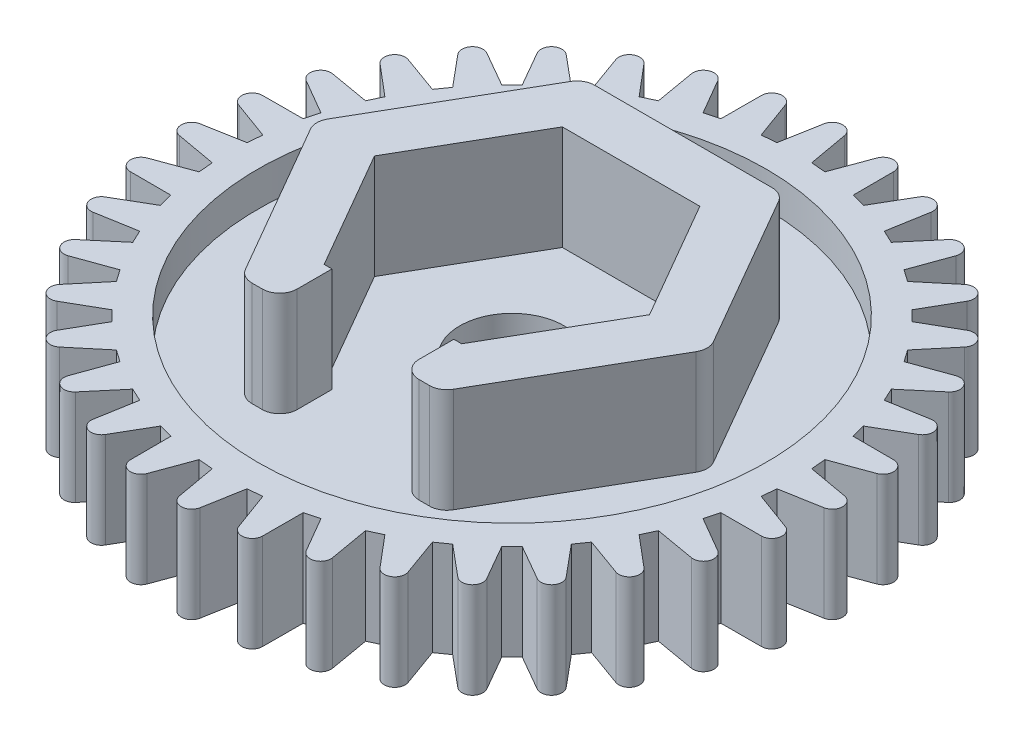
SolidWorks part; units mm, degrees
material "ABS"
ref_plane "Plano frontal" through (0, 0, 0) normal (0, 0, 1) x (1, 0, 0)
ref_plane "Plano superior" through (0, 0, 0) normal (0, 1, 0) x (1, 0, 0)
ref_plane "Plano direito" through (0, 0, 0) normal (1, 0, 0) x (0, 0, -1)
ref_plane "Plano1" through (0, 1, 0) normal (0, 1, 0) x (1, 0, 0)
sketch "Esboço1" plane through (0, 1, 0) normal (0, 1, 0) x (1, 0, 0)
  line L0 (-8.7959, 2.8872) -> (-7.9008, 2.3673)
  line L1 (-7.9008, 2.3673) -> (-7.8996, 1.9006)
  line L2 (-7.8996, 1.9006) -> (-9.061, 1.8976)
  line L3 (-9.1636, 1.3159) -> (-8.0732, 0.9158)
  line L4 (-8.0732, 0.9158) -> (-8.1096, 0.5)
  line L5 (-8.1096, 0.5) -> (-9.2529, 0.2953)
  line L6 (-9.2529, -0.2953) -> (-8.1096, -0.5)
  line L7 (-8.1096, -0.5) -> (-8.0732, -0.9158)
  line L8 (-8.0732, -0.9158) -> (-9.1636, -1.3159)
  line L9 (-9.061, -1.8976) -> (-7.8996, -1.9006)
  line L10 (-7.8996, -1.9006) -> (-7.9008, -2.3673)
  line L11 (-7.9008, -2.3673) -> (-8.7959, -2.8872)
  line L12 (-8.5939, -3.4422) -> (-7.4495, -3.2435)
  line L13 (-7.4495, -3.2435) -> (-7.2731, -3.6218)
  line L14 (-7.2731, -3.6218) -> (-8.1609, -4.3707)
  line L15 (-7.8656, -4.8822) -> (-6.7731, -4.4878)
  line L16 (-6.7731, -4.4878) -> (-6.5337, -4.8297)
  line L17 (-6.5337, -4.8297) -> (-7.2779, -5.7214)
  line L18 (-6.8983, -6.1738) -> (-5.8909, -5.5958)
  line L19 (-5.8909, -5.5958) -> (-5.5958, -5.8909)
  line L20 (-5.5958, -5.8909) -> (-6.1738, -6.8983)
  line L21 (-5.7214, -7.2779) -> (-4.8297, -6.5337)
  line L22 (-4.8297, -6.5337) -> (-4.4878, -6.7731)
  line L23 (-4.4878, -6.7731) -> (-4.8822, -7.8656)
  line L24 (-4.3707, -8.1609) -> (-3.6218, -7.2731)
  line L25 (-3.6218, -7.2731) -> (-3.2435, -7.4495)
  line L26 (-3.2435, -7.4495) -> (-3.4422, -8.5939)
  line L27 (-2.8872, -8.7959) -> (-2.3673, -7.9008)
  line L28 (-2.3673, -7.9008) -> (-1.9006, -7.8996)
  line L29 (-1.9006, -7.8996) -> (-1.8976, -9.061)
  line L30 (-1.3159, -9.1636) -> (-0.9158, -8.0732)
  line L31 (-0.9158, -8.0732) -> (-0.5, -8.1096)
  line L32 (-0.5, -8.1096) -> (-0.2953, -9.2529)
  line L33 (0.2953, -9.2529) -> (0.5, -8.1096)
  line L34 (0.5, -8.1096) -> (0.9158, -8.0732)
  line L35 (0.9158, -8.0732) -> (1.3159, -9.1636)
  line L36 (1.8976, -9.061) -> (1.9006, -7.8996)
  line L37 (1.9006, -7.8996) -> (2.3673, -7.9008)
  line L38 (2.3673, -7.9008) -> (2.8872, -8.7959)
  line L39 (3.4422, -8.5939) -> (3.2435, -7.4495)
  line L40 (3.2435, -7.4495) -> (3.6218, -7.2731)
  line L41 (3.6218, -7.2731) -> (4.3707, -8.1609)
  line L42 (4.8822, -7.8656) -> (4.4878, -6.7731)
  line L43 (4.4878, -6.7731) -> (4.8297, -6.5337)
  line L44 (4.8297, -6.5337) -> (5.7214, -7.2779)
  line L45 (6.1738, -6.8983) -> (5.5958, -5.8909)
  line L46 (5.5958, -5.8909) -> (5.8909, -5.5958)
  line L47 (5.8909, -5.5958) -> (6.8983, -6.1738)
  line L48 (7.2779, -5.7214) -> (6.5337, -4.8297)
  line L49 (6.5337, -4.8297) -> (6.7731, -4.4878)
  line L50 (6.7731, -4.4878) -> (7.8656, -4.8822)
  line L51 (8.1609, -4.3707) -> (7.2731, -3.6218)
  line L52 (7.2731, -3.6218) -> (7.4495, -3.2435)
  line L53 (7.4495, -3.2435) -> (8.5939, -3.4422)
  line L54 (8.7959, -2.8872) -> (7.9008, -2.3673)
  line L55 (7.9008, -2.3673) -> (7.8996, -1.9006)
  line L56 (7.8996, -1.9006) -> (9.061, -1.8976)
  line L57 (9.1636, -1.3159) -> (8.0732, -0.9158)
  line L58 (8.0732, -0.9158) -> (8.1096, -0.5)
  line L59 (8.1096, -0.5) -> (9.2529, -0.2953)
  line L60 (9.2529, 0.2953) -> (8.1096, 0.5)
  line L61 (8.1096, 0.5) -> (8.0732, 0.9158)
  line L62 (8.0732, 0.9158) -> (9.1636, 1.3159)
  line L63 (9.061, 1.8976) -> (7.8996, 1.9006)
  line L64 (7.8996, 1.9006) -> (7.9008, 2.3673)
  line L65 (7.9008, 2.3673) -> (8.7959, 2.8872)
  line L66 (8.5939, 3.4422) -> (7.4495, 3.2435)
  line L67 (7.4495, 3.2435) -> (7.2731, 3.6218)
  line L68 (7.2731, 3.6218) -> (8.1609, 4.3707)
  line L69 (7.8656, 4.8822) -> (6.7731, 4.4878)
  line L70 (6.7731, 4.4878) -> (6.5337, 4.8297)
  line L71 (6.5337, 4.8297) -> (7.2779, 5.7214)
  line L72 (6.8983, 6.1738) -> (5.8909, 5.5958)
  line L73 (5.8909, 5.5958) -> (5.5958, 5.8909)
  line L74 (5.5958, 5.8909) -> (6.1738, 6.8983)
  line L75 (5.7214, 7.2779) -> (4.8297, 6.5337)
  line L76 (4.8297, 6.5337) -> (4.4878, 6.7731)
  line L77 (4.4878, 6.7731) -> (4.8822, 7.8656)
  line L78 (4.3707, 8.1609) -> (3.6218, 7.2731)
  line L79 (3.6218, 7.2731) -> (3.2435, 7.4495)
  line L80 (3.2435, 7.4495) -> (3.4422, 8.5939)
  line L81 (2.8872, 8.7959) -> (2.3673, 7.9008)
  line L82 (2.3673, 7.9008) -> (1.9006, 7.8996)
  line L83 (1.9006, 7.8996) -> (1.8976, 9.061)
  line L84 (1.3159, 9.1636) -> (0.9158, 8.0732)
  line L85 (0.9158, 8.0732) -> (0.5, 8.1096)
  line L86 (0.5, 8.1096) -> (0.2953, 9.2529)
  line L87 (-0.2953, 9.2529) -> (-0.5, 8.1096)
  line L88 (-0.5, 8.1096) -> (-0.9158, 8.0732)
  line L89 (-0.9158, 8.0732) -> (-1.3159, 9.1636)
  line L90 (-1.8976, 9.061) -> (-1.9006, 7.8996)
  line L91 (-1.9006, 7.8996) -> (-2.3673, 7.9008)
  line L92 (-2.3673, 7.9008) -> (-2.8872, 8.7959)
  line L93 (-3.4422, 8.5939) -> (-3.2435, 7.4495)
  line L94 (-3.2435, 7.4495) -> (-3.6218, 7.2731)
  line L95 (-3.6218, 7.2731) -> (-4.3707, 8.1609)
  line L96 (-4.8822, 7.8656) -> (-4.4878, 6.7731)
  line L97 (-4.4878, 6.7731) -> (-4.8297, 6.5337)
  line L98 (-4.8297, 6.5337) -> (-5.7214, 7.2779)
  line L99 (-6.1738, 6.8983) -> (-5.5958, 5.8909)
  line L100 (-5.5958, 5.8909) -> (-5.8909, 5.5958)
  line L101 (-5.8909, 5.5958) -> (-6.8983, 6.1738)
  line L102 (-7.2779, 5.7214) -> (-6.5337, 4.8297)
  line L103 (-6.5337, 4.8297) -> (-6.7731, 4.4878)
  line L104 (-6.7731, 4.4878) -> (-7.8656, 4.8822)
  line L105 (-8.1609, 4.3707) -> (-7.2731, 3.6218)
  line L106 (-7.2731, 3.6218) -> (-7.4495, 3.2435)
  line L107 (-7.4495, 3.2435) -> (-8.5939, 3.4422)
  arc A0 (-9.061, 1.8976) -> (-9.1636, 1.3159) centre (-9.0602, 1.5976) ccw
  arc A1 (-9.2529, 0.2953) -> (-9.2529, -0.2953) centre (-9.2, 0) ccw
  arc A2 (-9.1636, -1.3159) -> (-9.061, -1.8976) centre (-9.0602, -1.5976) ccw
  arc A3 (-8.7959, -2.8872) -> (-8.5939, -3.4422) centre (-8.6452, -3.1466) ccw
  arc A4 (-8.1609, -4.3707) -> (-7.8656, -4.8822) centre (-7.9674, -4.6) ccw
  arc A5 (-7.2779, -5.7214) -> (-6.8983, -6.1738) centre (-7.0476, -5.9136) ccw
  arc A6 (-6.1738, -6.8983) -> (-5.7214, -7.2779) centre (-5.9136, -7.0476) ccw
  arc A7 (-4.8822, -7.8656) -> (-4.3707, -8.1609) centre (-4.6, -7.9674) ccw
  arc A8 (-3.4422, -8.5939) -> (-2.8872, -8.7959) centre (-3.1466, -8.6452) ccw
  arc A9 (-1.8976, -9.061) -> (-1.3159, -9.1636) centre (-1.5976, -9.0602) ccw
  arc A10 (-0.2953, -9.2529) -> (0.2953, -9.2529) centre (0, -9.2) ccw
  arc A11 (1.3159, -9.1636) -> (1.8976, -9.061) centre (1.5976, -9.0602) ccw
  arc A12 (2.8872, -8.7959) -> (3.4422, -8.5939) centre (3.1466, -8.6452) ccw
  arc A13 (4.3707, -8.1609) -> (4.8822, -7.8656) centre (4.6, -7.9674) ccw
  arc A14 (5.7214, -7.2779) -> (6.1738, -6.8983) centre (5.9136, -7.0476) ccw
  arc A15 (6.8983, -6.1738) -> (7.2779, -5.7214) centre (7.0476, -5.9136) ccw
  arc A16 (7.8656, -4.8822) -> (8.1609, -4.3707) centre (7.9674, -4.6) ccw
  arc A17 (8.5939, -3.4422) -> (8.7959, -2.8872) centre (8.6452, -3.1466) ccw
  arc A18 (9.061, -1.8976) -> (9.1636, -1.3159) centre (9.0602, -1.5976) ccw
  arc A19 (9.2529, -0.2953) -> (9.2529, 0.2953) centre (9.2, 0) ccw
  arc A20 (9.1636, 1.3159) -> (9.061, 1.8976) centre (9.0602, 1.5976) ccw
  arc A21 (8.7959, 2.8872) -> (8.5939, 3.4422) centre (8.6452, 3.1466) ccw
  arc A22 (8.1609, 4.3707) -> (7.8656, 4.8822) centre (7.9674, 4.6) ccw
  arc A23 (7.2779, 5.7214) -> (6.8983, 6.1738) centre (7.0476, 5.9136) ccw
  arc A24 (6.1738, 6.8983) -> (5.7214, 7.2779) centre (5.9136, 7.0476) ccw
  arc A25 (4.8822, 7.8656) -> (4.3707, 8.1609) centre (4.6, 7.9674) ccw
  arc A26 (3.4422, 8.5939) -> (2.8872, 8.7959) centre (3.1466, 8.6452) ccw
  arc A27 (1.8976, 9.061) -> (1.3159, 9.1636) centre (1.5976, 9.0602) ccw
  arc A28 (0.2953, 9.2529) -> (-0.2953, 9.2529) centre (0, 9.2) ccw
  arc A29 (-1.3159, 9.1636) -> (-1.8976, 9.061) centre (-1.5976, 9.0602) ccw
  arc A30 (-2.8872, 8.7959) -> (-3.4422, 8.5939) centre (-3.1466, 8.6452) ccw
  arc A31 (-4.3707, 8.1609) -> (-4.8822, 7.8656) centre (-4.6, 7.9674) ccw
  arc A32 (-5.7214, 7.2779) -> (-6.1738, 6.8983) centre (-5.9136, 7.0476) ccw
  arc A33 (-6.8983, 6.1738) -> (-7.2779, 5.7214) centre (-7.0476, 5.9136) ccw
  arc A34 (-7.8656, 4.8822) -> (-8.1609, 4.3707) centre (-7.9674, 4.6) ccw
  arc A35 (-8.5939, 3.4422) -> (-8.7959, 2.8872) centre (-8.6452, 3.1466) ccw
extrude "Ressalto-extrusão1" add sketch "Esboço1" against normal blind 2.75
hole_wizard "Furo com folga de M121" positions "Esboço3" profile "Esboço2" hole size "M12" standard "Ansi Metric"
sketch "Esboço3" plane through (0, 1, 0) normal (0, 1, 0) x (1, 0, 0)
  point P0 (0, 0)
sketch "Esboço2" plane through (0, 1, 0) normal (1, 0, 0) x (0, 0, 1)
  line L0 (0, 0) -> (0, 1)
  line L1 (0, 1) -> (7.3, 1)
  line L2 (7.3, 1) -> (7.3, 0)
  line L5 (7.3, 0) -> (0, 0)
  line L10 (0, 1) -> (-7.3, 1) construction
  line L11 (0, -6.35) -> (0, 107.95) construction
  dimension "Hole Dia." = 14.6
  dimension "Hole Depth" = 1
  dimension "Drill Angle" = 180
sketch "Esboço4" plane through (0, 0, 0) normal (0, 1, 0) x (-1, 0, 0)
  line L0 (1.75, 4.9208) -> (2.841, 4.9208)
  line L1 (2.841, 4.9208) -> (5.6821, 0)
  line L2 (5.6821, 0) -> (2.841, -4.9208)
  line L3 (2.841, -4.9208) -> (-2.841, -4.9208)
  line L4 (-2.841, -4.9208) -> (-5.6821, 0)
  line L5 (-5.6821, 0) -> (-2.841, 4.9208)
  line L6 (-2.841, 4.9208) -> (-1.75, 4.9208)
  line L7 (-1.75, 4.9208) -> (-1.75, 3.4208)
  line L8 (-1.75, 3.4208) -> (-1.975, 3.4208)
  line L9 (-1.975, 3.4208) -> (-3.95, 0)
  line L10 (-3.95, 0) -> (-1.975, -3.4208)
  line L11 (-1.975, -3.4208) -> (1.975, -3.4208)
  line L12 (1.975, -3.4208) -> (3.95, 0)
  line L13 (3.95, 0) -> (1.975, 3.4208)
  line L14 (1.975, 3.4208) -> (1.75, 3.4208)
  line L15 (1.75, 3.4208) -> (1.75, 4.9208)
extrude "Ressalto-extrusão2" add sketch "Esboço4" along normal blind 3
draft "Inclinação1" type of draft neutral plane draft angle 15.151 faces to draft 1 face at (2.1339, -0.375, -7.9002) neutral plane through (1.9006, -1.75, -7.8996) neutral plane normal (1, 0, -0.0026) parameters "D1"=15.151
draft "Inclinação2" type of draft neutral plane draft angle 15.151 faces to draft 1 face at (7.9002, -0.375, -2.1339) neutral plane through (9.061, -1.75, -1.8976) neutral plane normal (0.0026, 0, -1) parameters "D1"=15.151
draft "Inclinação3" type of draft neutral plane draft angle 15.151 faces to draft 1 face at (7.9002, -0.375, 2.1339) neutral plane through (7.8996, -1.75, 1.9006) neutral plane normal (0.0026, 0, 1) parameters "D1"=15.151
draft "Inclinação4" type of draft neutral plane draft angle 15.151 faces to draft 1 face at (2.1339, -0.375, 7.9002) neutral plane through (1.8976, -1.75, 9.061) neutral plane normal (1, 0, 0.0026) parameters "D1"=15.151
draft "Inclinação5" type of draft neutral plane draft angle 15.151 faces to draft 1 face at (-2.1339, -0.375, 7.9002) neutral plane through (-1.9006, -1.75, 7.8996) neutral plane normal (-1, 0, 0.0026) parameters "D1"=15.151
draft "Inclinação6" type of draft neutral plane draft angle 15.151 faces to draft 1 face at (-7.9002, -0.375, 2.1339) neutral plane through (-9.061, -1.75, 1.8976) neutral plane normal (-0.0026, 0, 1) parameters "D1"=15.151
draft "Inclinação7" type of draft neutral plane draft angle 15.151 faces to draft 1 face at (-7.9002, -0.375, -2.1339) neutral plane through (-7.8996, -1.75, -1.9006) neutral plane normal (-0.0026, 0, -1) parameters "D1"=15.151
draft "Inclinação8" type of draft neutral plane draft angle 15.151 faces to draft 1 face at (-2.1339, -0.375, -7.9002) neutral plane through (-1.8976, -1.75, -9.061) neutral plane normal (-1, 0, -0.0026) parameters "D1"=15.151
ref_plane "Plano2" through (0, 0, 0) normal (0, 0, -1) x (-1, 0, 0)
sketch "Esboço5" plane through (0, 0, 0) normal (0, 0, -1) x (-1, 0, 0)
  line L0 (-7.3, -2) -> (0, -2)
  line L1 (0, -2) -> (0, -1.75)
  line L2 (0, -1.75) -> (-7.3, -1.75)
  line L3 (-7.3, -1.75) -> (-7.3, -2)
  line L4 (0, -2) -> (0, -1.75) construction
revolve "Revolução1" add sketch "Esboço5" angle 360 about L4
hole_wizard "Furo de diâmetro Ø3.0 (3)1" positions "Esboço7" profile "Esboço6" hole size "Ø3.0" standard "Ansi Metric"
sketch "Esboço7" plane through (0, 0, 0) normal (0, 1, 0) x (1, 0, 0)
  point P0 (0, 0)
sketch "Esboço6" plane through (0, 0, 0) normal (1, 0, 0) x (0, 0, 1)
  line L0 (0, 0) -> (0, 2)
  line L1 (0, 2) -> (1.5, 2)
  line L2 (1.5, 2) -> (1.5, 0)
  line L5 (1.5, 0) -> (0, 0)
  line L11 (0, -6.35) -> (0, 107.95) construction
  dimension "Thru Hole Dia." = 3
  dimension "Thru Hole Depth" = 2
fillet "Filete1" radius 0.5 8 edges at (-1.75, 1.5, 4.9208) (-5.6821, 1.5, 0) (-2.841, 1.5, -4.9208) (2.841, 1.5, 4.9208) (-2.841, 1.5, 4.9208) (5.6821, 1.5, 0) (1.75, 1.5, 4.9208) (2.841, 1.5, -4.9208)
